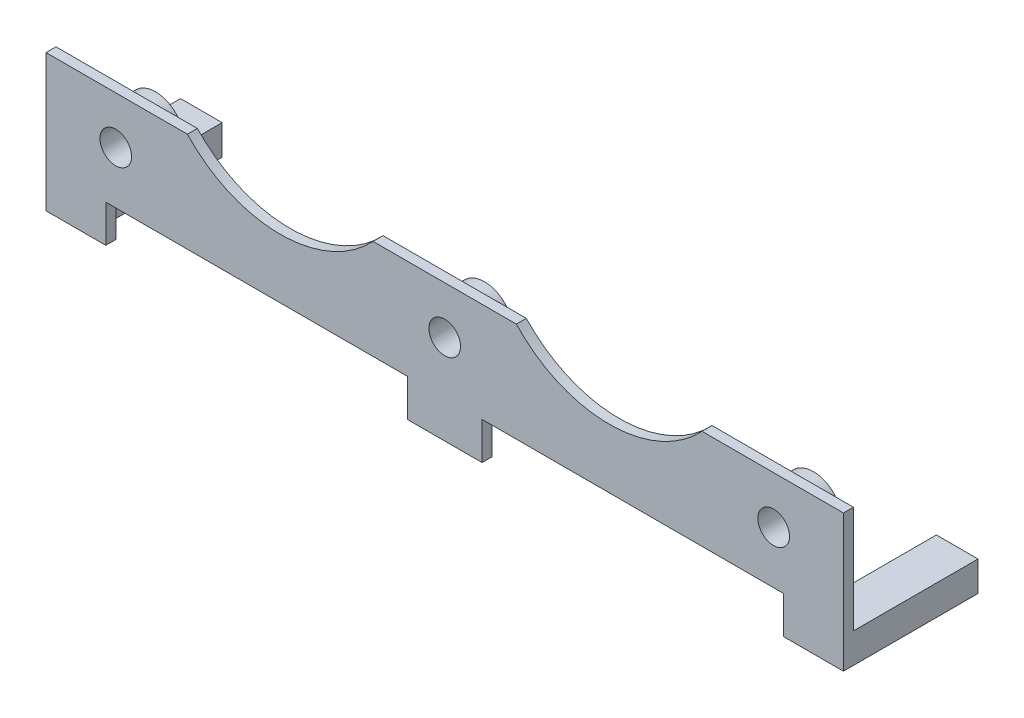
SolidWorks part; units mm, degrees
ref_plane "Alzado" through (0, 0, 0) normal (0, 0, 1) x (1, 0, 0)
ref_plane "Planta" through (0, 0, 0) normal (0, 1, 0) x (1, 0, 0)
ref_plane "Vista lateral" through (0, 0, 0) normal (1, 0, 0) x (0, 0, -1)
sketch "Croquis1" plane through (0, 0, 0) normal (0, 0, 1) x (1, 0, 0)
  line L0 (72.9839, -4.5) -> (-77.3987, -4.5) construction
  line L1 (80, -15) -> (-80, -15)
  line L2 (80, -15) -> (80, 15)
  line L3 (80, 15) -> (-80, 15)
  line L4 (-80, -15) -> (-80, 15)
  line L5 (80, -15) -> (-80, 15) construction
  line L6 (80, 15) -> (-80, -15) construction
  line L7 (0, 18.4553) -> (0, -14.2527) construction
  line L8 (0, -4.5) -> (66, -4.5) construction
  line L9 (0, -4.5) -> (-66, -4.5) construction
  line L10 (68, -22.5) -> (80, -22.5)
  line L11 (-80, 15) -> (80, 15)
  line L12 (-80, 15) -> (-80, 5)
  line L13 (-80, 5) -> (80, 5)
  line L14 (80, 15) -> (80, 5)
  line L15 (-68, -4.5) -> (-80, -4.5)
  line L16 (-68, -4.5) -> (-68, -22.5)
  line L17 (-68, -22.5) -> (-80, -22.5)
  line L18 (-80, -4.5) -> (-80, -22.5)
  line L19 (80, -4.5) -> (80, -22.5)
  line L20 (68, -4.5) -> (80, -4.5)
  line L21 (68, -4.5) -> (68, -22.5)
  line L23 (-7.5, -15) -> (7.5, -15)
  line L24 (-7.5, -15) -> (-7.5, -22.5)
  line L25 (-7.5, -22.5) -> (7.5, -22.5)
  line L26 (7.5, -15) -> (7.5, -22.5)
  circle A0 centre (0, -4.5) radius 3.175
  circle A1 centre (66, -4.5) radius 3.175
  circle A2 centre (0, -4.5) radius 3.175
  circle A3 centre (-66, -4.5) radius 3.175
  point P0 (0, 0)
  dimension "D2" = 6.35
  dimension "D1" = 4.5
  dimension "D5" = 66
  dimension "D6" = 66
  dimension "D7" = 160
  dimension "D8" = 30
  dimension "D9" = 10
  dimension "D10" = 18
  dimension "D11" = 12
  dimension "D12" = 15
  dimension "D3" = 2
  dimension "D4" = 2
extrude "Saliente-Extruir1" add sketch "Croquis1" along normal blind 2 contours L21 L20 L2 L13 L4 L15 L16 L1 A3 A1 A0 | L1 L18 L17 L16 | L16 L15 L4 L1 | L20 L21 L1 L2 | L1 L21 L10 L19 | L26 L1 L24 L25
sketch "Croquis2" plane through (0, 0, 0) normal (0, 0, -1) x (-1, 0, 0)
  line L1 (-80, -22.5) -> (-71.65, -22.5)
  line L2 (-80, -22.5) -> (-80, -16.5)
  line L3 (-80, -16.5) -> (-71.65, -16.5)
  line L4 (-71.65, -22.5) -> (-71.65, -16.5)
  line L5 (0, -36.7743) -> (0, 17.2243) construction
  line L6 (-68, -22.5) -> (-80, -22.5) construction
  line L7 (80, -16.5) -> (71.65, -16.5)
  line L8 (71.65, -22.5) -> (71.65, -16.5)
  line L9 (80, -22.5) -> (71.65, -22.5)
  line L10 (80, -22.5) -> (80, -16.5)
  dimension "D1" = 6
  dimension "D2" = 143.3
extrude "Saliente-Extruir2" add sketch "Croquis2" along normal blind 25
sketch "Croquis3" plane through (0, 0, 0) normal (0, 0, -1) x (-1, 0, 0)
  line L0 (80, 5) -> (-80, 5) construction
  line L1 (0, 0) -> (-66, 0) construction
  line L3 (-66, -4.5) -> (-66, 12.9664) construction
  line L4 (-33, 0) -> (-33, 22.4307) construction
  line L5 (0, -12.8017) -> (0, 26.1395) construction
  line L6 (-51.627, 5) -> (-14.373, 5)
  line L7 (51.627, 5) -> (14.373, 5)
  arc A0 (-51.627, 5) -> (-14.373, 5) centre (-33, 22.4307) ccw
  arc A1 (-51.627, 5) -> (-14.373, 5) centre (-33, -12.4307) cw
  arc A2 (51.627, 5) -> (14.373, 5) centre (33, 22.4307) cw
  line M12 (80, 5) -> (-80, 5)
  dimension "D1" = 25.5106
  dimension "D2" = 22.4307
extrude "Cortar-Extruir1" cut sketch "Croquis3" against normal blind 32.5 contours A2 M12 | A0 M12
sketch "Croquis4" plane through (0, 0, 0) normal (0, 0, -1) x (-1, 0, 0)
  circle A0 centre (-66, -4.5) radius 3.175 construction
  circle A1 centre (-66, -4.5) radius 3.175
  circle A2 centre (0, -4.5) radius 3.175 construction
  circle A3 centre (0, -4.5) radius 3.175
  circle A4 centre (66, -4.5) radius 3.175 construction
  circle A5 centre (66, -4.5) radius 3.175
  circle A6 centre (-66, -4.5) radius 5.675
  circle A7 centre (0, -4.5) radius 5.675
  circle A8 centre (66, -4.5) radius 5.675
  dimension "D1" = 2.5
  dimension "D2" = 2.5
  dimension "D3" = 2.5
extrude "Saliente-Extruir3" add sketch "Croquis4" along normal blind 6
